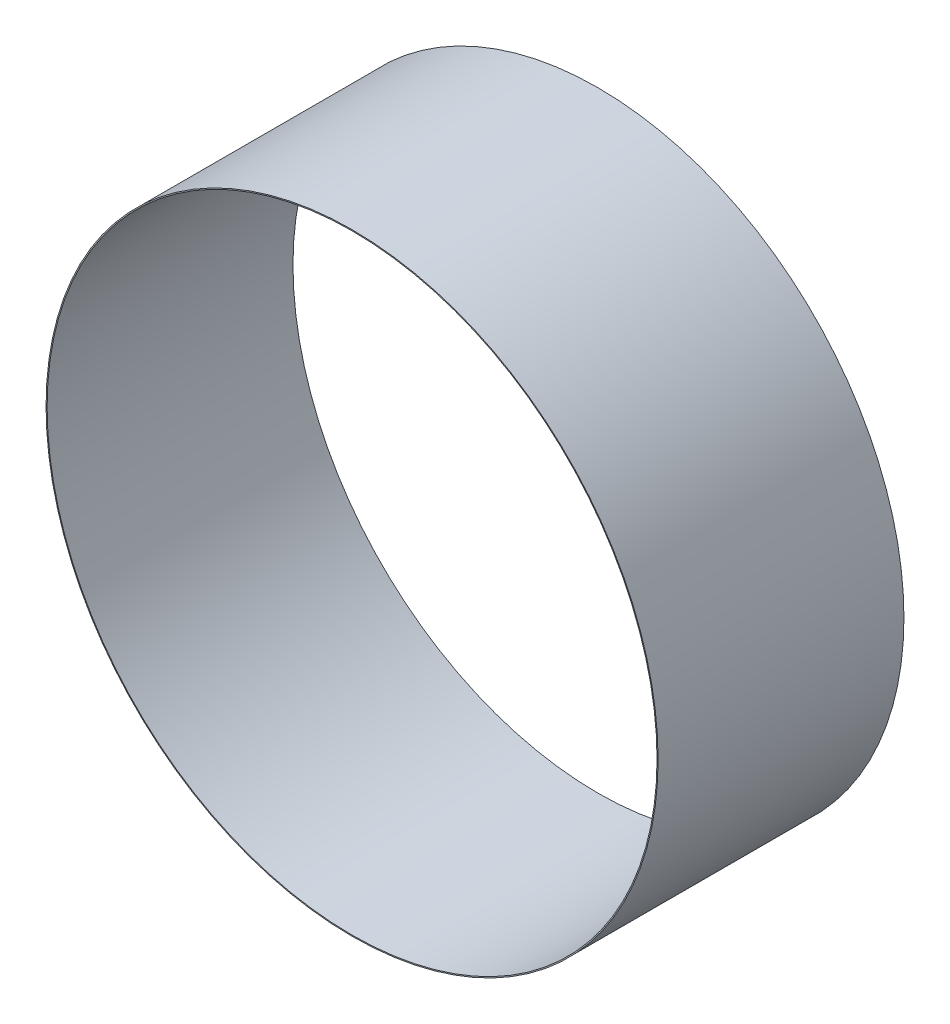
SolidWorks part; units mm, degrees
ref_plane "Ebene vorne" through (0, 0, 0) normal (0, 0, 1) x (1, 0, 0)
ref_plane "Ebene oben" through (0, 0, 0) normal (0, 1, 0) x (1, 0, 0)
ref_plane "Ebene rechts" through (0, 0, 0) normal (1, 0, 0) x (0, 0, -1)
sketch "Skizze1" plane through (0, 0, 0) normal (0, 0, 1) x (1, 0, 0)
  circle A0 centre (0, 0) radius 60.78
  circle A1 centre (0, 0) radius 60.9908
  point P4 (0, 60.78)
  point P5 (60.78, 0)
  point P6 (0, 0)
  point P7 (0, -60.78)
  point P8 (-60.78, 0)
  point P9 (64.6349, 67.9913)
extrude "Aufsatz-Linear austragen1" add sketch "Skizze1" along normal blind 49
